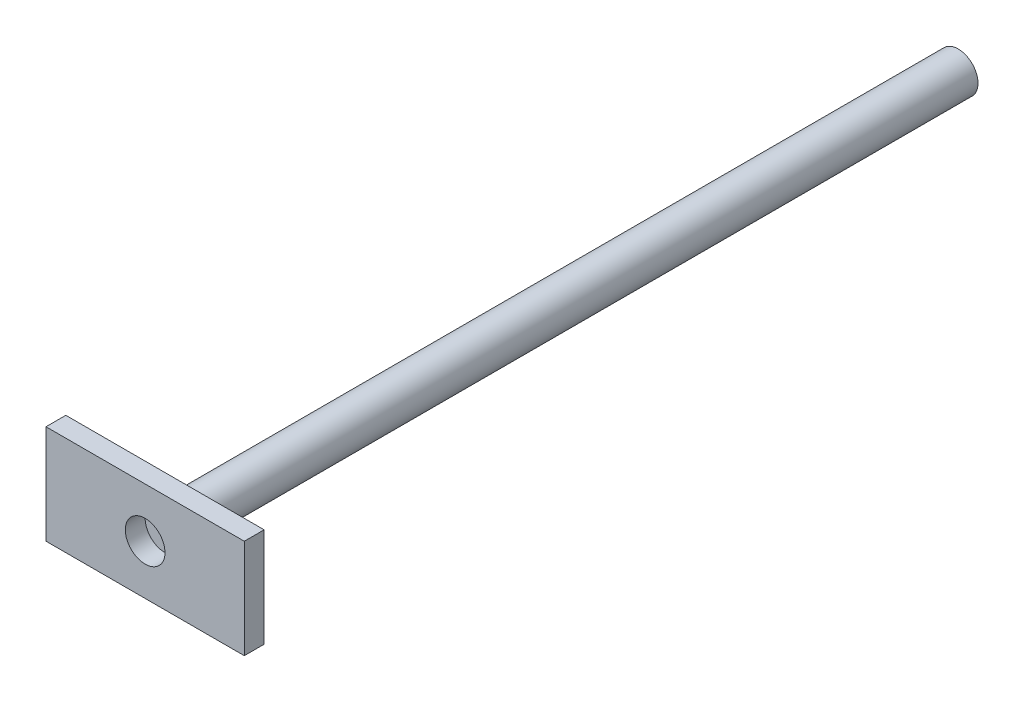
SolidWorks part; units mm, degrees
ref_plane "前视基准面" through (0, 0, 0) normal (0, 0, 1) x (1, 0, 0)
ref_plane "上视基准面" through (0, 0, 0) normal (0, 1, 0) x (1, 0, 0)
ref_plane "右视基准面" through (0, 0, 0) normal (1, 0, 0) x (0, 0, -1)
sketch "草图1" plane through (0, 0, 0) normal (0, 0, 1) x (1, 0, 0)
  circle A0 centre (0, 0) radius 10
  dimension "D1" = 20
extrude "凸台-拉伸1" add sketch "草图1" along normal blind 400
sketch "草图2" plane through (0, 0, 400) normal (0, 0, 1) x (1, 0, 0)
  line L1 (50, -25) -> (-50, -25)
  line L2 (50, -25) -> (50, 25)
  line L3 (50, 25) -> (-50, 25)
  line L4 (-50, -25) -> (-50, 25)
  line L5 (50, -25) -> (-50, 25) construction
  line L6 (50, 25) -> (-50, -25) construction
  circle A0 centre (0, 0) radius 10
  point P0 (0, 0)
  dimension "D1" = 100
  dimension "D2" = 50
extrude "凸台-拉伸2" add sketch "草图2" along normal blind 10
